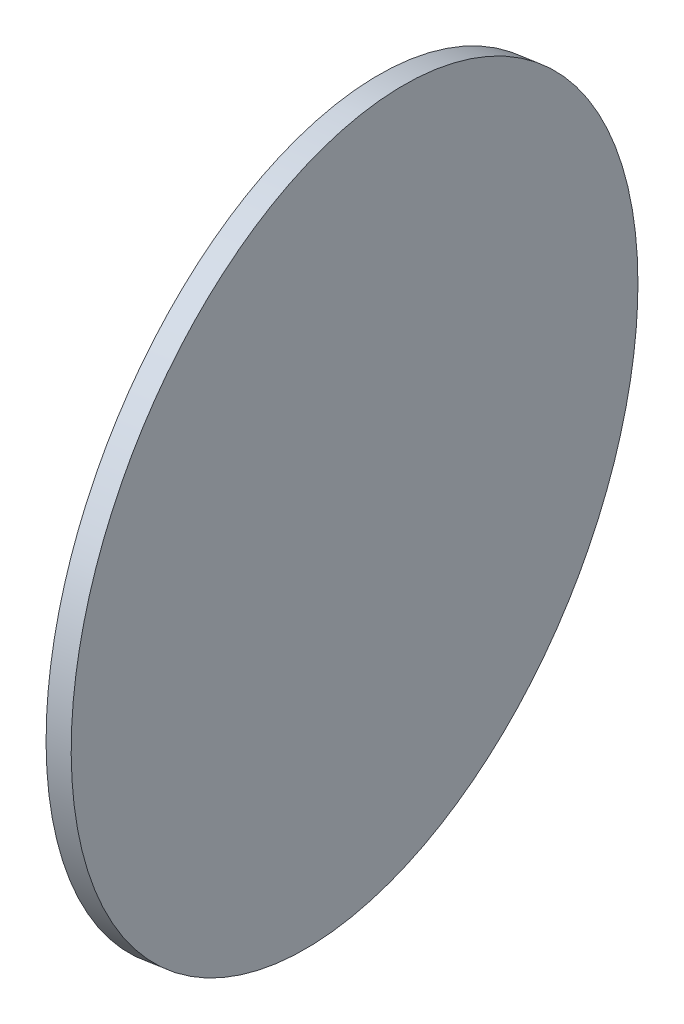
SolidWorks part; units mm, degrees
ref_plane "Front Plane" through (0, 0, 0) normal (1, 0, 0) x (0, 1, 0)
ref_plane "Top Plane" through (0, 0, 0) normal (0, 0, 1) x (0, 1, 0)
ref_plane "Right Plane" through (0, 0, 0) normal (0, 1, 0) x (-1, 0, 0)
sketch "Sketch1" plane through (0, 0, 0) normal (1, 0, 0) x (0, 1, 0)
  circle A0 centre (0, 0) radius 15.875
  dimension "D1" = 31.75
sketch "Sketch2" plane through (0, 0, 0) normal (0, 1, 0) x (-1, 0, 0)
  line L0 (2.9014, -16.4545) -> (-2.9014, 16.4545) construction
  line L2 (0, 15.875) -> (0, -15.875) construction
  point P4 (0, 0)
  dimension "D1" = 10
ref_plane "Plane1" through (0, 0, 0) normal (0.9848, 0, -0.1736) x (0.1736, 0, 0.9848)
sketch "Sketch3" plane through (0, 0, 0) normal (0, 1, 0) x (-1, 0, 0)
  line L0 (0, 15.875) -> (0, -15.875) construction
  line L1 (0, 15.875) -> (0, -15.875)
  line L2 (0, 15.875) -> (-2.7463, 15.875)
  line L3 (0, -15.875) -> (2.7463, -15.875)
  point P2 (-2.7463, 15.875)
  point P4 (0, 0)
sketch "Sketch4" plane through (0, 0, 0) normal (0.9848, 0, -0.1736) x (0.1736, 0, 0.9848)
  ellipse E0 centre (0, 0) end of major axis (-16.1107, 0) minor radius 15.875
  ellipse E1 centre (0, 0) end of major axis (0, -15.875) minor radius 15.6338 construction
extrude "Boss-Extrude1" add sketch "Sketch4" along normal mid plane 1
